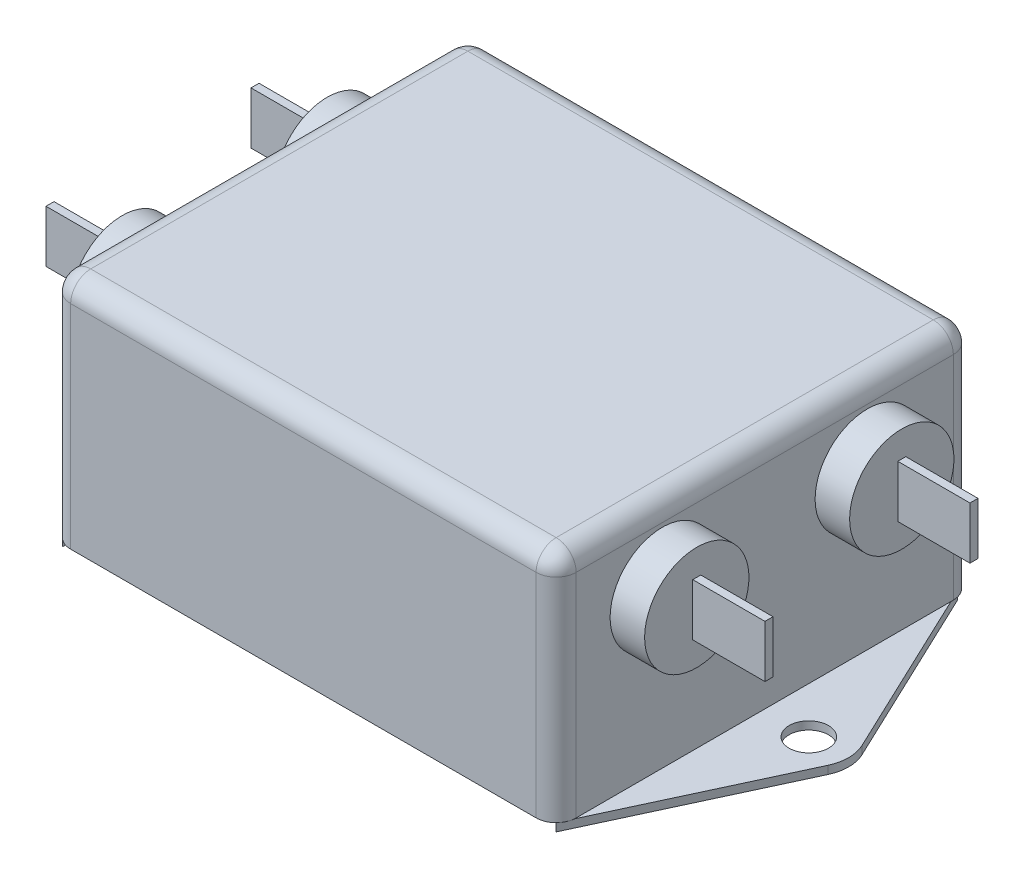
SolidWorks part; units mm, degrees
material "Nikiel"
ref_plane "Front" through (0, 0, 0) normal (0, 0, 1) x (1, 0, 0)
ref_plane "Top" through (0, 0, 0) normal (0, 1, 0) x (1, 0, 0)
ref_plane "Right" through (0, 0, 0) normal (1, 0, 0) x (0, 0, -1)
sketch "Szkic1" plane through (0, 0, 0) normal (0, 1, 0) x (1, 0, 0)
  line L1 (-29.2772, 30.5677) -> (33.7228, 30.5677)
  line L2 (-29.2772, 30.5677) -> (-29.2772, -21.4323)
  line L3 (-29.2772, -21.4323) -> (33.7228, -21.4323)
  line L4 (33.7228, 30.5677) -> (33.7228, -21.4323)
  dimension "D1" = 52
  dimension "D2" = 63
extrude "Dodanie-wyciągnięcie1" add sketch "Szkic1" along normal blind 29
fillet "Zaokrąglenie1" radius 2.5 8 edges at (-29.2772, 14.5, -30.5677) (33.7228, 14.5, -30.5677) (33.7228, 14.5, 21.4323) (-29.2772, 14.5, 21.4323) (-29.2772, 29, -4.5677) (2.2228, 29, 21.4323) (33.7228, 29, -4.5677) (2.2228, 29, -30.5677)
sketch "Szkic2" plane through (0, 0, 0) normal (0, -1, 0) x (1, 0, 0)
  line L0 (2.2228, 21.4323) -> (2.2228, -30.5677) construction
  line L1 (-26.7772, 21.4323) -> (31.2228, 21.4323) construction
  line L2 (31.2228, -30.5677) -> (-26.7772, -30.5677) construction
  line L3 (44.7228, -4.5677) -> (-40.2772, -4.5677) construction
  line L6 (-39.2892, -2.4398) -> (-28.5449, 20.7001)
  line L7 (-28.5449, 20.7001) -> (-28.5449, -29.3126)
  line L8 (-28.5449, -29.3126) -> (-39.2721, -6.6876)
  line L9 (32.9906, 20.7001) -> (32.9906, -29.3126)
  line L10 (32.9906, -29.3126) -> (43.7177, -6.6876)
  line L11 (43.7348, -2.4398) -> (32.9906, 20.7001)
  arc A1 (-26.7772, 21.4323) -> (-29.2772, 18.9323) centre (-26.7772, 18.9323) ccw construction
  arc A2 (33.7228, 18.9323) -> (31.2228, 21.4323) centre (31.2228, 18.9323) ccw construction
  arc A3 (43.7348, -2.4398) -> (43.7177, -6.6876) centre (39.1998, -4.5455) cw
  arc A4 (-39.2892, -2.4398) -> (-39.2721, -6.6876) centre (-34.7542, -4.5455) ccw
  dimension "D1" = 5
extrude "Dodanie-wyciągnięcie2" add sketch "Szkic2" along normal blind 1
sketch "Szkic3" plane through (0, 0, 0) normal (0, -1, 0) x (1, 0, 0)
  circle A1 centre (-35.0272, -4.3063) radius 2.45
  circle A2 centre (39.4728, -4.3063) radius 2.45
extrude "Wytnij-wyciągnięcie6" cut sketch "Szkic3" along normal through all
sketch "Szkic4" plane through (-29.2772, 0, 0) normal (-1, 0, 0) x (0, 0, 1)
  line L0 (-4.5677, 26.5) -> (-4.5677, -9.1394) construction
  line L1 (18.9323, 26.5) -> (-28.0677, 26.5) construction
  line L2 (-4.5677, 19.5) -> (8.2068, 19.5) construction
  line L3 (8.2068, 19.5) -> (-17.2443, 19.5) construction
  circle A1 centre (8.2068, 19.5) radius 6.5
  circle A2 centre (-17.3422, 19.5) radius 6.5
  dimension "D1" = 7
extrude "Dodanie-wyciągnięcie3" add sketch "Szkic4" along normal blind 4.3
sketch "Szkic5" plane through (-33.5772, 0, 0) normal (-1, 0, 0) x (0, 0, 1)
  line L0 (8.2068, 19.5) -> (8.2068, 13) construction
  line L1 (8.7068, 16.25) -> (8.7068, 22.75)
  line L2 (8.7068, 22.75) -> (7.7068, 22.75)
  line L3 (7.7068, 16.25) -> (8.7068, 16.25)
  line L4 (7.7068, 16.25) -> (7.7068, 22.75)
  circle A0 centre (8.2068, 19.5) radius 6.5 construction
extrude "Dodanie-wyciągnięcie4" add sketch "Szkic5" along normal blind 9
ref_plane "Płaszczyzna1" through (0, 0, -4.5677) normal (0, 0, -1) x (-1, 0, 0)
mirror "Lustro1" about plane through (0, 0, -4.5677) normal (0, 0, -1) of "Dodanie-wyciągnięcie4"
ref_plane "Płaszczyzna2" through (2.2228, 0, 0) normal (-1, 0, 0) x (0, 0, 1)
mirror "Lustro2" about plane through (2.2228, 0, 0) normal (-1, 0, 0) of "Dodanie-wyciągnięcie3"
mirror "Lustro3" about plane through (2.2228, 0, 0) normal (-1, 0, 0) of "Dodanie-wyciągnięcie4"
mirror "Lustro4" about plane through (2.2228, 0, 0) normal (-1, 0, 0) of "Lustro1"
